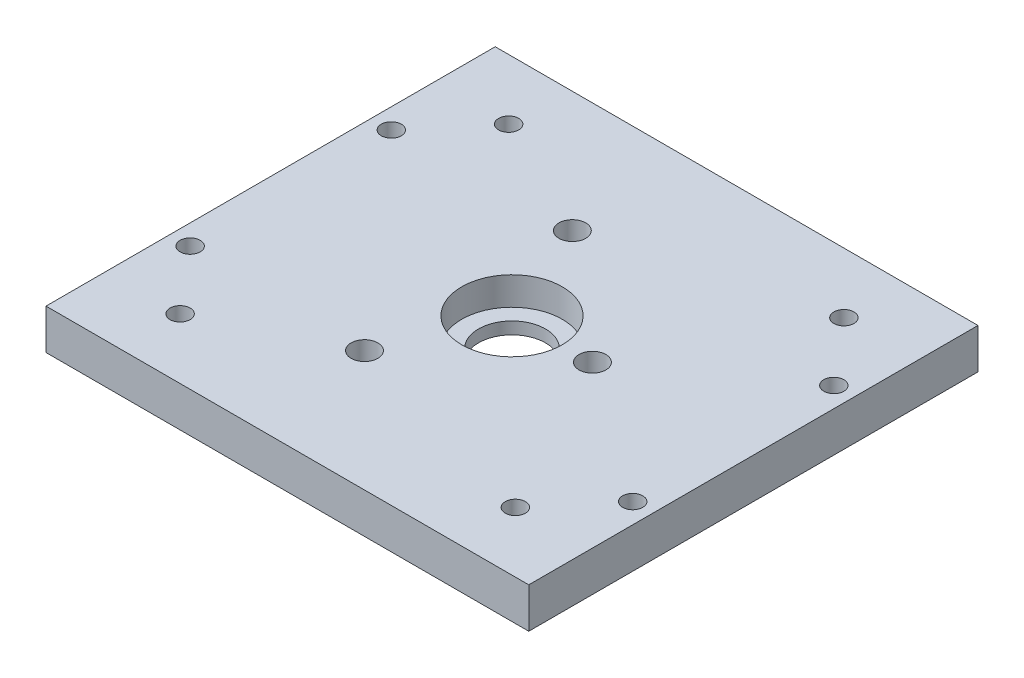
SolidWorks part; units mm, degrees
ref_plane "Front Plane" through (0, 0, 0) normal (0, 0, 1) x (1, 0, 0)
ref_plane "Top Plane" through (0, 0, 0) normal (0, 1, 0) x (1, 0, 0)
ref_plane "Right Plane" through (0, 0, 0) normal (1, 0, 0) x (0, 0, -1)
sketch "Sketch1" plane through (0, 0, 0) normal (0, 1, 0) x (1, 0, 0)
  line L1 (-36, 33.5) -> (36, 33.5)
  line L2 (-36, 33.5) -> (-36, -33.5)
  line L3 (-36, -33.5) -> (36, -33.5)
  line L4 (36, 33.5) -> (36, -33.5)
  line L5 (-36, 33.5) -> (36, -33.5) construction
  line L6 (-36, -33.5) -> (36, 33.5) construction
  point P0 (0, 0)
  dimension "D1" = 72
  dimension "D2" = 67
extrude "Boss-Extrude1" add sketch "Sketch1" along normal blind 6
sketch "Sketch2" plane through (0, 6, 0) normal (0, 1, 0) x (1, 0, 0)
  line L0 (0, 0) -> (0, 16.7962) construction
  circle A0 centre (0, 0) radius 5
  circle A5 centre (-6.5, 15.5) radius 2
  circle A6 centre (-6.5, -15.5) radius 2
  dimension "D1" = 10
  dimension "D2" = 4
  dimension "D3" = 4
extrude "Cut-Extrude1" cut sketch "Sketch2" against normal blind 6
sketch "Sketch3" plane through (0, 6, 0) normal (0, 1, 0) x (1, 0, 0)
  circle A0 centre (0, 0) radius 7.5
  dimension "D1" = 15
extrude "Cut-Extrude2" cut sketch "Sketch3" against normal blind 4.2
sketch "Sketch5" plane through (0, 6, 0) normal (0, 1, 0) x (1, 0, 0)
  circle A1 centre (12, 0) radius 2
  dimension "D2" = 4
  dimension "D1" = 12
extrude "Cut-Extrude3" cut sketch "Sketch5" against normal blind 10
sketch "Sketch6" plane through (0, 0, 0) normal (0, -1, 0) x (1, 0, 0)
  line L0 (-21.7979, 0) -> (27.2766, 0) construction
  line L1 (0, 0) -> (0, 38.6154) construction
  line L2 (-36, 33.5) -> (36, 33.5) construction
  line L3 (-36, -33.5) -> (-36, 33.5) construction
  circle A1 centre (-25, 24.5) radius 1.5
  circle A2 centre (25, 24.5) radius 1.5
  circle A4 centre (-33, 15) radius 1.5
  circle A5 centre (33, 15) radius 1.5
  circle A6 centre (33, -15) radius 1.5
  circle A7 centre (-33, -15) radius 1.5
  circle A9 centre (25, -24.5) radius 1.5
  circle A10 centre (-25, -24.5) radius 1.5
  dimension "D4" = 3
  dimension "D7" = 3
  dimension "D3" = 9
  dimension "D6" = 25
  dimension "D8" = 3
  dimension "D9" = 15
extrude "Cut-Extrude4" cut sketch "Sketch6" against normal blind 10
